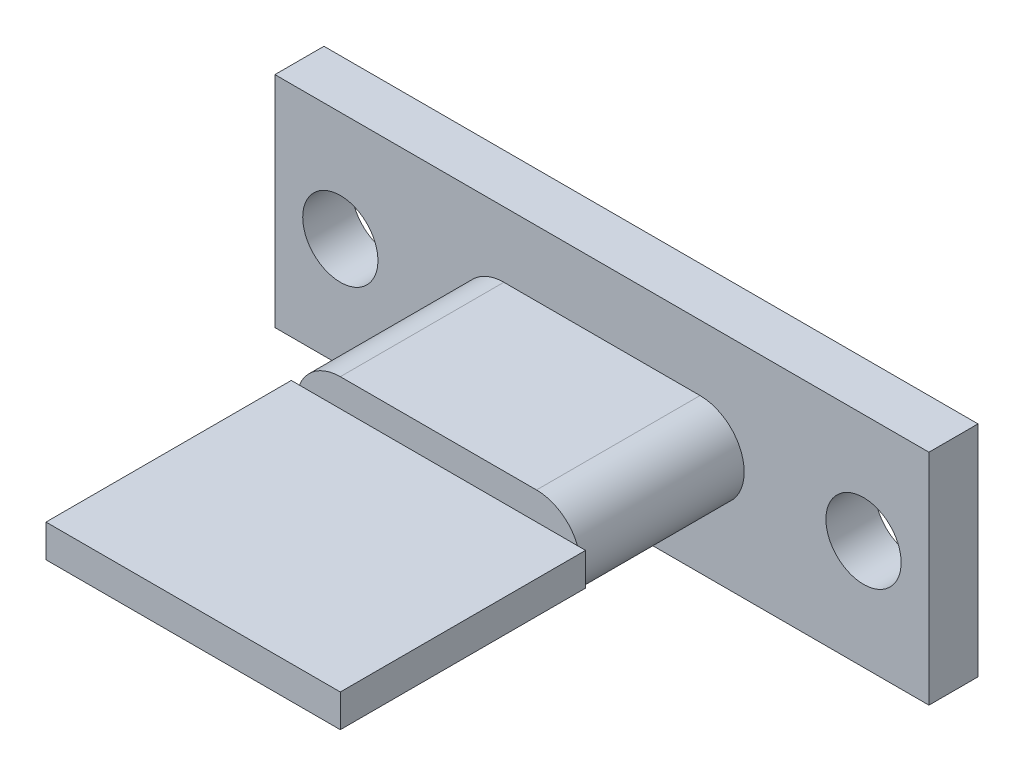
SolidWorks part; units mm, degrees
ref_plane "Front Plane" through (0, 0, 0) normal (0, 0, 1) x (1, 0, 0)
ref_plane "Top Plane" through (0, 0, 0) normal (0, 1, 0) x (1, 0, 0)
ref_plane "Right Plane" through (0, 0, 0) normal (1, 0, 0) x (0, 0, -1)
sketch "Sketch1" plane through (0, 0, 0) normal (0, 0, 1) x (1, 0, 0)
  line L1 (-10, -3.35) -> (10, -3.35)
  line L2 (-10, -3.35) -> (-10, 3.35)
  line L3 (-10, 3.35) -> (10, 3.35)
  line L4 (10, -3.35) -> (10, 3.35)
  line L5 (-10, -3.35) -> (10, 3.35) construction
  line L6 (-10, 3.35) -> (10, -3.35) construction
  point P0 (0, 0)
  dimension "D1" = 20
  dimension "D2" = 6.7
extrude "Boss-Extrude1" add sketch "Sketch1" along normal blind 1.5
sketch "Sketch2" plane through (0, 0, 0) normal (0, 0, -1) x (-1, 0, 0)
  line L0 (-3, 0) -> (3, 0) construction
  line L1 (-3, 1.25) -> (3, 1.25)
  line L2 (-3, -1.25) -> (3, -1.25)
  line L3 (-10, 0) -> (10, 0) construction
  line L4 (-10, -3.35) -> (-10, 3.35) construction
  line L5 (10, 3.35) -> (10, -3.35) construction
  line L6 (-8, 0) -> (0, 3.35) construction
  line L7 (-10, 3.35) -> (10, 3.35) construction
  line L8 (0, 3.35) -> (8, 0) construction
  arc A0 (-3, 1.25) -> (-3, -1.25) centre (-3, 0) ccw
  arc A1 (3, -1.25) -> (3, 1.25) centre (3, 0) ccw
  circle A2 centre (-8, 0) radius 1.15
  circle A3 centre (8, 0) radius 1.15
  point P2 (0, 0)
  dimension "D2" = 8.5
  dimension "D3" = 2.3
  dimension "D1" = 2.5
  dimension "D4" = 16
  dimension "D5" = 0.85
extrude "Cut-Extrude1" cut sketch "Sketch2" against normal blind 1.5
sketch "Sketch3" plane through (0, 0, 1.5) normal (0, 0, 1) x (1, 0, 0)
  line L0 (3, 1.35) -> (-3, 1.35)
  line L1 (-3, -1.35) -> (3, -1.35)
  line L2 (3, 1.25) -> (-3, 1.25)
  line L3 (-3, -1.25) -> (3, -1.25)
  line L4 (3, 1.25) -> (-3, 1.25)
  line L5 (-3, -1.25) -> (3, -1.25)
  arc A0 (-3, 1.35) -> (-3, -1.35) centre (-3, 0) ccw
  arc A1 (3, -1.35) -> (3, 1.35) centre (3, 0) ccw
  arc A2 (3, -1.25) -> (3, 1.25) centre (3, 0) ccw
  arc A3 (-3, 1.25) -> (-3, -1.25) centre (-3, 0) ccw
  arc A4 (3, -1.25) -> (3, 1.25) centre (3, 0) ccw
  arc A5 (-3, 1.25) -> (-3, -1.25) centre (-3, 0) ccw
  dimension "D1" = 0
  dimension "D2" = 0.1
extrude "Boss-Extrude2" add sketch "Sketch3" along normal blind 5
sketch "Sketch4" plane through (0, 0, 6.5) normal (0, 0, 1) x (1, 0, 0)
  line L2 (3, 1.35) -> (-3, 1.35)
  line L3 (-3, -1.35) -> (3, -1.35)
  line L4 (3, 1.35) -> (-3, 1.35)
  line L5 (-3, -1.35) -> (3, -1.35)
  arc A2 (3, -1.35) -> (3, 1.35) centre (3, 0) ccw
  arc A3 (-3, 1.35) -> (-3, -1.35) centre (-3, 0) ccw
  arc A4 (3, -1.35) -> (3, 1.35) centre (3, 0) ccw
  arc A5 (-3, 1.35) -> (-3, -1.35) centre (-3, 0) ccw
  dimension "D1" = 0
extrude "Boss-Extrude3" add sketch "Sketch4" against normal blind 1
sketch "Sketch5" plane through (0, 0, 5.5) normal (0, 0, -1) x (-1, 0, 0)
  line L1 (-3, -0.3) -> (3, -0.3)
  line L2 (-3, -0.3) -> (-3, 0.3)
  line L3 (-3, 0.3) -> (3, 0.3)
  line L4 (3, -0.3) -> (3, 0.3)
  line L5 (-3, -0.3) -> (3, 0.3) construction
  line L6 (-3, 0.3) -> (3, -0.3) construction
  point P0 (0, 0)
  dimension "D1" = 0.6
  dimension "D2" = 6
extrude "Boss-Extrude4" add sketch "Sketch5" along normal offset from surface (4.5 mm away) 1 up to face at (-9.15, 0, 0)
sketch "Sketch6" plane through (0, 0, 6.5) normal (0, 0, 1) x (1, 0, 0)
  line L1 (-4.5, -0.5) -> (4.5, -0.5)
  line L2 (-4.5, -0.5) -> (-4.5, 0.5)
  line L3 (-4.5, 0.5) -> (4.5, 0.5)
  line L4 (4.5, -0.5) -> (4.5, 0.5)
  line L5 (-4.5, -0.5) -> (4.5, 0.5) construction
  line L6 (-4.5, 0.5) -> (4.5, -0.5) construction
  point P0 (0, 0)
  dimension "D1" = 1
  dimension "D2" = 9
extrude "Boss-Extrude5" add sketch "Sketch6" along normal blind 7.5
